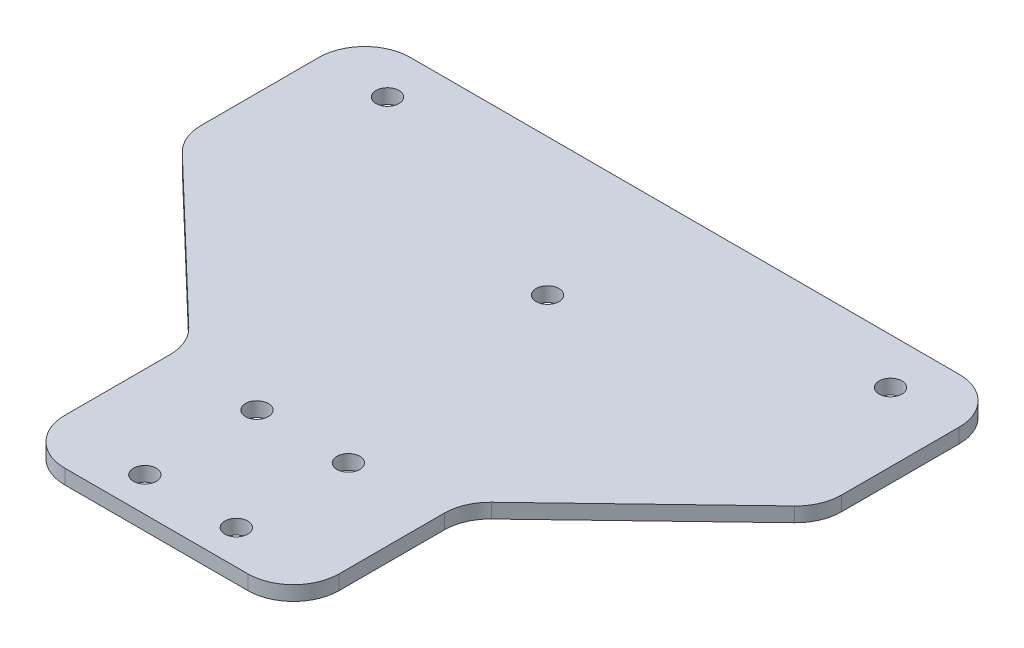
SolidWorks part; units mm, degrees
ref_plane "Front Plane" through (0, 0, 0) normal (0, 0, 1) x (1, 0, 0)
ref_plane "Top Plane" through (0, 0, 0) normal (0, 1, 0) x (1, 0, 0)
ref_plane "Right Plane" through (0, 0, 0) normal (1, 0, 0) x (0, 0, -1)
sketch "Sketch1" plane through (0, 0, 0) normal (0, 1, 0) x (1, 0, 0)
  line L0 (0, 0) -> (40, 0)
  line L1 (40, 0) -> (90, 0)
  line L2 (90, 115.5509) -> (90, 75.5509)
  line L3 (90, 115.5509) -> (-50, 115.5509)
  line L4 (-50, 115.5509) -> (-50, 0)
  line L5 (90, 75.5509) -> (90, 40)
  line L6 (90, 40) -> (90, 0)
  line L7 (90, 40) -> (-50, 40) construction
  line L8 (90, 75.5509) -> (-50, 75.5509) construction
  line L9 (30, 0) -> (30, 40) construction
  line L10 (10, 40) -> (10, 0) construction
  line L11 (90, 105.5509) -> (-50, 105.5509) construction
  line L12 (90, 85.5509) -> (-50, 85.5509) construction
  line L13 (-50, 0) -> (0, 0)
  line L14 (10, 7.5) -> (30, 7.5) construction
  line L15 (10, 32) -> (30, 32) construction
  circle A0 centre (-35, 105.5509) radius 2.5
  circle A1 centre (75, 105.5509) radius 2.5
  circle A2 centre (20, 85.5509) radius 2.5
  circle A3 centre (10, 7.5) radius 2.5
  circle A4 centre (30, 7.5) radius 2.5
  circle A5 centre (10, 32) radius 2.5
  circle A6 centre (30, 32) radius 2.5
  dimension "D7" = 10
  dimension "D9" = 5
  dimension "D4" = 5
  dimension "D2" = 40
  dimension "D3" = 40
  dimension "D5" = 40
  dimension "D6" = 50
  dimension "D8" = 10
  dimension "D10" = 10
  dimension "D11" = 10
  dimension "D12" = 15
  dimension "D13" = 15
  dimension "D14" = 7.5
  dimension "D15" = 32
extrude "Boss-Extrude1" add sketch "Sketch1" along normal blind 3.18
sketch "Sketch3" plane through (0, 0, 0) normal (0, -1, 0) x (1, 0, 0)
  line L0 (90, -75.5509) -> (50, -37.2311)
  line L1 (90, 0) -> (90, -115.5509) construction
  line L3 (50, -37.2311) -> (90, -37.2311) construction
  line L4 (90, -37.2311) -> (90, -75.5509)
  line L5 (-50, -37.2311) -> (-10, -37.2311) construction
  line L7 (-10, -37.2311) -> (-50, -75.5509)
  line L8 (-50, -115.5509) -> (-50, 0) construction
  line L9 (-50, -75.5509) -> (-50, -37.2311)
  line L10 (90, -75.5509) -> (-50, -75.5509) construction
  line L11 (90, -115.5509) -> (-50, -115.5509) construction
  line L12 (-50, -37.2311) -> (-50, 0)
  line L13 (-50, 0) -> (-10, 0)
  line L14 (-10, 0) -> (-10, -37.2311)
  line L15 (50, -37.2311) -> (50, 0)
  line L16 (50, 0) -> (90, 0)
  line L17 (90, 0) -> (90, -37.2311)
  dimension "D1" = 40
  dimension "D2" = 40
extrude "Cut-Extrude1" cut sketch "Sketch3" against normal through all
fillet "Fillet1" radius 10 8 edges at (90, 1.59, -75.5509) (-50, 1.59, -75.5509) (-50, 1.59, -115.5509) (90, 1.59, -115.5509) (-10, 1.59, -37.2311) (50, 1.59, -37.2311) (-10, 1.59, 0) (50, 1.59, 0)
